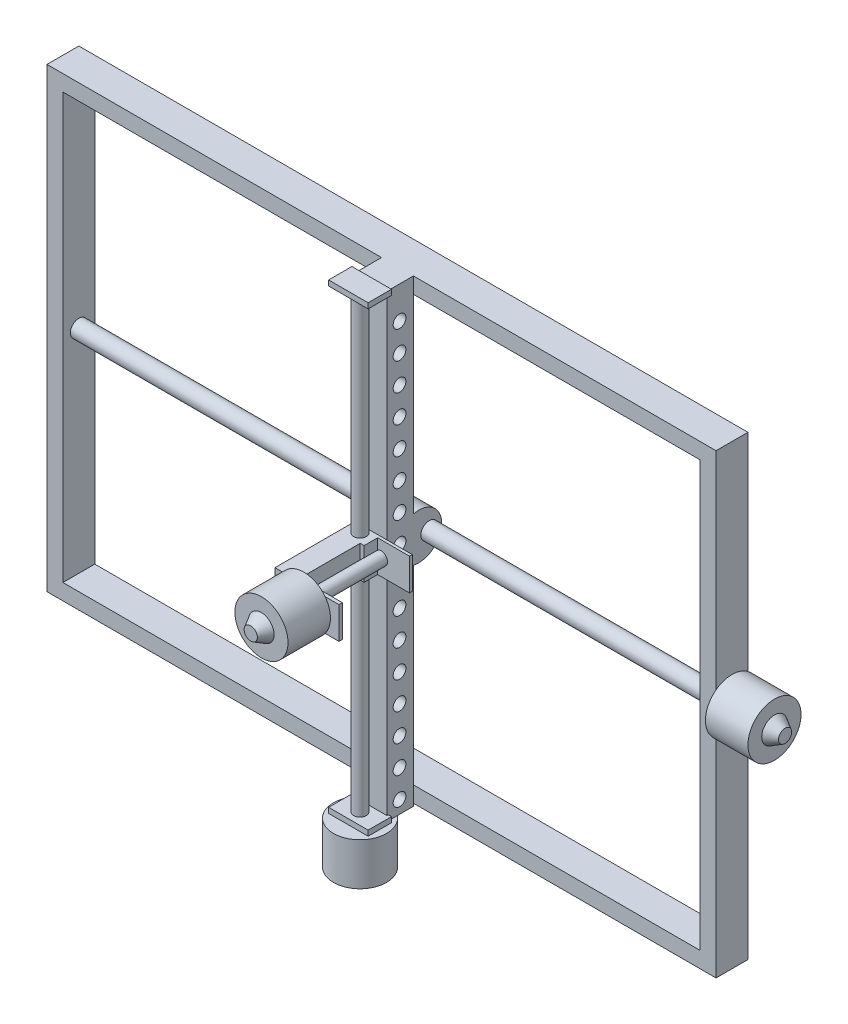
SolidWorks part; units mm, degrees
ref_plane "Alzado" through (0, 0, 0) normal (0, 0, 1) x (1, 0, 0)
ref_plane "Planta" through (0, 0, 0) normal (0, 1, 0) x (1, 0, 0)
ref_plane "Vista lateral" through (0, 0, 0) normal (1, 0, 0) x (0, 0, -1)
sketch "Croquis1" plane through (0, 0, 0) normal (0, 0, 1) x (1, 0, 0)
  line L0 (-315, 215) -> (-315, -215)
  line L1 (-300, 200) -> (300, 200)
  line L2 (-300, 200) -> (-300, -200)
  line L3 (-300, -200) -> (300, -200)
  line L4 (300, 200) -> (300, -200)
  line L5 (-300, 200) -> (300, -200) construction
  line L6 (-300, -200) -> (300, 200) construction
  line L7 (-315, -215) -> (315, -215)
  line L8 (315, 215) -> (315, -215)
  line L9 (-315, 215) -> (315, 215)
  point P0 (0, 0)
  dimension "D1" = 600
  dimension "D2" = 400
  dimension "D3" = 15
extrude "Saliente-Extruir1" add sketch "Croquis1" along normal blind 30
sketch "Croquis2" plane through (315, 0, 0) normal (1, 0, 0) x (0, 0, -1)
  circle A0 centre (-15, 0) radius 25
extrude "Saliente-Extruir2" add sketch "Croquis2" along normal blind 40
sketch "Croquis3" plane through (355, 0, 0) normal (1, 0, 0) x (0, 0, -1)
  circle A0 centre (-15, 0) radius 8
extrude "Saliente-Extruir3" add sketch "Croquis3" against normal up to surface (655 mm away) up to face at (-300, 0, 15)
sketch "Croquis4" plane through (0, 0, 0) normal (1, 0, 0) x (0, 0, -1)
  line L1 (-30, 215) -> (-54.9923, 215)
  line L2 (-30, 215) -> (-30, -217.5191)
  line L3 (-30, -217.5191) -> (-54.9923, -217.5191)
  line L4 (-54.9923, 215) -> (-54.9923, -217.5191)
extrude "Saliente-Extruir4" add sketch "Croquis4" along normal blind 30
sketch "Croquis5" plane through (30, 0, 0) normal (1, 0, 0) x (0, 0, -1)
  circle A0 centre (-24.8754, 0) radius 21.4875
extrude "Saliente-Extruir5" add sketch "Croquis5" against normal blind 30
sketch "Croquis6" plane through (0, -217.5191, 0) normal (0, -1, 0) x (1, 0, 0)
  line L1 (-4.1173, 75.6922) -> (33.0715, 75.6922)
  line L2 (-4.1173, 75.6922) -> (-4.1173, 53.7331)
  line L3 (-4.1173, 53.7331) -> (33.0715, 53.7331)
  line L4 (33.0715, 75.6922) -> (33.0715, 53.7331)
extrude "Saliente-Extruir6" add sketch "Croquis6" against normal blind 5
mirror "Simetría1" about plane through (0, 0, 0) normal (0, 1, 0) of "Saliente-Extruir6"
sketch "Croquis7" plane through (0, -217.5191, 0) normal (0, -1, 0) x (1, 0, 0)
  circle A0 centre (14.4771, 64.7127) radius 25
extrude "Saliente-Extruir7" add sketch "Croquis7" along normal blind 40
sketch "Croquis8" plane through (0, -257.5191, 0) normal (0, -1, 0) x (1, 0, 0)
  circle A0 centre (14.4771, 64.7127) radius 6
  dimension "D1" = 12
extrude "Saliente-Extruir9" add sketch "Croquis8" against normal up to surface (470.0382 mm away) up to face at (14.7385, 212.5191, 59.5377)
sketch "Croquis9" plane through (0, 0, 0) normal (0, 1, 0) x (1, 0, 0)
  line L1 (2.7262, -57.7418) -> (26.6795, -57.7418)
  line L2 (2.7262, -57.7418) -> (2.7262, -73.0828)
  line L3 (2.7262, -73.0828) -> (26.6795, -73.0828)
  line L4 (26.6795, -57.7418) -> (26.6795, -73.0828)
extrude "Saliente-Extruir10" add sketch "Croquis9" along normal mid plane 30
sketch "Croquis10" plane through (0, 0, 73.0828) normal (0, 0, 1) x (1, 0, 0)
  line L0 (2.7262, -15) -> (26.6795, -15) construction
  line L1 (2.7262, 15) -> (22.9922, 15)
  line L2 (2.7262, 15) -> (2.7262, -15)
  line L3 (2.7262, -15) -> (22.9922, -15)
  line L4 (22.9922, 15) -> (22.9922, -15)
extrude "Saliente-Extruir11" add sketch "Croquis10" along normal blind 60
sketch "Croquis11" plane through (0, 0, 133.0828) normal (0, 0, 1) x (1, 0, 0)
  line L0 (30, 212.5191) -> (30, -212.5191) construction
  circle A0 centre (30, 0) radius 25
extrude "Saliente-Extruir12" add sketch "Croquis11" along normal blind 40
sketch "Croquis12" plane through (26.6795, 0, 0) normal (1, 0, 0) x (0, 0, -1)
  line L0 (-73.0828, -15) -> (-57.7418, -15) construction
  line L1 (-57.7418, 15) -> (-60.3488, 15)
  line L2 (-57.7418, 15) -> (-57.7418, -15)
  line L3 (-57.7418, -15) -> (-60.3488, -15)
  line L4 (-60.3488, 15) -> (-60.3488, -15)
extrude "Saliente-Extruir13" add sketch "Croquis12" along normal blind 30
sketch "Croquis13" plane through (0, 0, 173.0828) normal (0, 0, 1) x (1, 0, 0)
  circle A0 centre (30, 0) radius 6
  dimension "D1" = 12
extrude "Saliente-Extruir14" add sketch "Croquis13" against normal up to surface (112.7339 mm away) up to face at (49.1795, 3.75, 60.3488)
sketch "Croquis14" plane through (22.9922, 0, 0) normal (1, 0, 0) x (0, 0, -1)
  line L0 (-133.0828, -15) -> (-73.0828, -15) construction
  line L1 (-133.0828, 15) -> (-129.8685, 15)
  line L2 (-133.0828, 15) -> (-133.0828, -15)
  line L3 (-133.0828, -15) -> (-129.8685, -15)
  line L4 (-129.8685, 15) -> (-129.8685, -15)
extrude "Saliente-Extruir15" add sketch "Croquis14" along normal blind 40
sketch "Croquis16" plane through (355, 0, 0) normal (1, 0, 0) x (0, 0, -1)
  circle A0 centre (-15, 0) radius 12
extrude "Saliente-Extruir16" add sketch "Croquis16" along normal blind 10 draft 30
sketch "Croquis17" plane through (0, -257.5191, 0) normal (0, -1, 0) x (1, 0, 0)
  circle A0 centre (14.4771, 64.7127) radius 12
extrude "Saliente-Extruir17" add sketch "Croquis17" along normal blind 10 draft 30
sketch "Croquis18" plane through (0, 0, 173.0828) normal (0, 0, 1) x (1, 0, 0)
  circle A0 centre (29.9304, 0) radius 12
extrude "Saliente-Extruir18" add sketch "Croquis18" along normal blind 10 draft 30
sketch "Croquis19" plane through (30, 0, 0) normal (1, 0, 0) x (0, 0, -1)
  circle A0 centre (-43.0316, -205.4125) radius 6
  circle A1 centre (-43.0316, -179.4125) radius 6
  circle A2 centre (-43.0316, -153.4125) radius 6
  circle A3 centre (-43.0316, -127.4125) radius 6
  circle A4 centre (-43.0316, -101.4125) radius 6
  circle A5 centre (-43.0316, -75.4125) radius 6
  circle A6 centre (-43.0316, -49.4125) radius 6
  circle A7 centre (-43.0316, -23.4125) radius 6
  circle A8 centre (-43.0316, 2.5875) radius 6
  circle A9 centre (-43.0316, 28.5875) radius 6
  circle A10 centre (-43.0316, 54.5875) radius 6
  circle A11 centre (-43.0316, 80.5875) radius 6
  circle A12 centre (-43.0316, 106.5875) radius 6
  circle A13 centre (-43.0316, 132.5875) radius 6
  circle A14 centre (-43.0316, 158.5875) radius 6
  circle A15 centre (-43.0316, 184.5875) radius 6
  dimension "D1" = 16
extrude "Cortar-Extruir1" cut sketch "Croquis19" against normal blind 70
